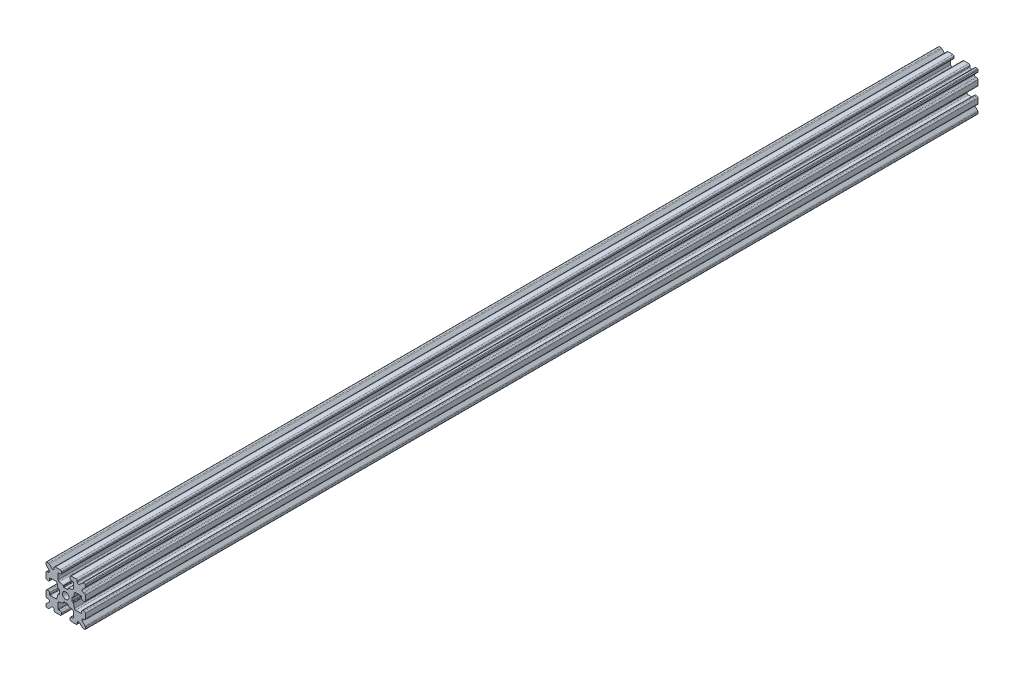
SolidWorks part; units mm, degrees
ref_plane "Alzado" through (0, 0, 0) normal (0, 0, 1) x (1, 0, 0)
ref_plane "Planta" through (0, 0, 0) normal (0, 1, 0) x (1, 0, 0)
ref_plane "Vista lateral" through (0, 0, 0) normal (1, 0, 0) x (0, 0, -1)
ref_plane "Plano1" through (0, 0, -150) normal (0, 0, -1) x (-1, 0, 0)
sketch "Croquis1" plane through (0, 0, -150) normal (0, 0, -1) x (-1, 0, 0)
  line L0 (-2.9, -5.9) -> (-2.9, -3.8003)
  line L1 (-2.5094, -3.3124) -> (-0.9818, -2.97)
  line L2 (-0.8255, -2.7749) -> (-0.8255, -2.5471)
  line L3 (-0.6255, -2.3471) -> (0.6255, -2.3471)
  line L4 (0.8255, -2.5471) -> (0.8255, -2.7749)
  line L5 (0.9818, -2.97) -> (2.5094, -3.3124)
  line L6 (2.9, -3.8003) -> (2.9, -5.9)
  line L7 (2.7, -6.1) -> (2.1, -6.1)
  line L8 (1.6, -6.6) -> (1.6, -7)
  line L9 (2.1, -7.5) -> (3.9, -7.5)
  line L10 (4.4, -7) -> (4.4, -6.6678)
  line L11 (5.2536, -6.3142) -> (6.2929, -7.3536)
  line L12 (6.6464, -7.5) -> (7.25, -7.5)
  line L13 (7.5, -7.25) -> (7.5, -6.6464)
  line L14 (7.3536, -6.2929) -> (6.3142, -5.2536)
  line L15 (6.6678, -4.4) -> (7, -4.4)
  line L16 (7.5, -3.9) -> (7.5, -2.1)
  line L17 (7, -1.6) -> (6.6, -1.6)
  line L18 (6.1, -2.1) -> (6.1, -2.7)
  line L19 (5.9, -2.9) -> (3.8003, -2.9)
  line L20 (3.3124, -2.5094) -> (2.97, -0.9818)
  line L21 (2.7749, -0.8255) -> (2.5471, -0.8255)
  line L22 (2.3471, -0.6255) -> (2.3471, 0.6255)
  line L23 (2.5471, 0.8255) -> (2.7749, 0.8255)
  line L24 (2.97, 0.9818) -> (3.3124, 2.5094)
  line L25 (3.8003, 2.9) -> (5.9, 2.9)
  line L26 (6.1, 2.7) -> (6.1, 2.1)
  line L27 (6.6, 1.6) -> (7, 1.6)
  line L28 (7.5, 2.1) -> (7.5, 3.9)
  line L29 (7, 4.4) -> (6.6678, 4.4)
  line L30 (6.3142, 5.2536) -> (7.3536, 6.2929)
  line L31 (7.5, 6.6464) -> (7.5, 7.25)
  line L32 (7.25, 7.5) -> (6.6464, 7.5)
  line L33 (6.2929, 7.3536) -> (5.2536, 6.3142)
  line L34 (4.4, 6.6678) -> (4.4, 7)
  line L35 (3.9, 7.5) -> (2.1, 7.5)
  line L36 (1.6, 7) -> (1.6, 6.6)
  line L37 (2.1, 6.1) -> (2.7, 6.1)
  line L38 (2.9, 5.9) -> (2.9, 3.8003)
  line L39 (2.5094, 3.3124) -> (0.9818, 2.97)
  line L40 (0.8255, 2.7749) -> (0.8255, 2.5471)
  line L41 (0.6255, 2.3471) -> (-0.6255, 2.3471)
  line L42 (-0.8255, 2.5471) -> (-0.8255, 2.7749)
  line L43 (-0.9818, 2.97) -> (-2.5094, 3.3124)
  line L44 (-2.9, 3.8003) -> (-2.9, 5.9)
  line L45 (-2.7, 6.1) -> (-2.1, 6.1)
  line L46 (-1.6, 6.6) -> (-1.6, 7)
  line L47 (-2.1, 7.5) -> (-3.9, 7.5)
  line L48 (-4.4, 7) -> (-4.4, 6.6678)
  line L49 (-5.2536, 6.3142) -> (-6.2929, 7.3536)
  line L50 (-6.6464, 7.5) -> (-7.25, 7.5)
  line L51 (-7.5, 7.25) -> (-7.5, 6.6464)
  line L52 (-7.3536, 6.2929) -> (-6.3142, 5.2536)
  line L53 (-6.6678, 4.4) -> (-7, 4.4)
  line L54 (-7.5, 3.9) -> (-7.5, 2.1)
  line L55 (-7, 1.6) -> (-6.6, 1.6)
  line L56 (-6.1, 2.1) -> (-6.1, 2.7)
  line L57 (-5.9, 2.9) -> (-3.8003, 2.9)
  line L58 (-3.3124, 2.5094) -> (-2.97, 0.9818)
  line L59 (-2.7749, 0.8255) -> (-2.5471, 0.8255)
  line L60 (-2.3471, 0.6255) -> (-2.3471, -0.6255)
  line L61 (-2.5471, -0.8255) -> (-2.7749, -0.8255)
  line L62 (-2.97, -0.9818) -> (-3.3124, -2.5094)
  line L63 (-3.8003, -2.9) -> (-5.9, -2.9)
  line L64 (-6.1, -2.7) -> (-6.1, -2.1)
  line L65 (-6.6, -1.6) -> (-7, -1.6)
  line L66 (-7.5, -2.1) -> (-7.5, -3.9)
  line L67 (-7, -4.4) -> (-6.6678, -4.4)
  line L68 (-6.3142, -5.2536) -> (-7.3536, -6.2929)
  line L69 (-7.5, -6.6464) -> (-7.5, -7.25)
  line L70 (-7.25, -7.5) -> (-6.6464, -7.5)
  line L71 (-6.2929, -7.3536) -> (-5.2536, -6.3142)
  line L72 (-4.4, -6.6678) -> (-4.4, -7)
  line L73 (-3.9, -7.5) -> (-2.1, -7.5)
  line L74 (-1.6, -7) -> (-1.6, -6.6)
  line L75 (-2.1, -6.1) -> (-2.7, -6.1)
  circle A0 centre (0, 0) radius 1.25
  arc A1 (-2.9, -3.8003) -> (-2.5094, -3.3124) centre (-2.4, -3.8003) cw
  arc A2 (-0.9818, -2.97) -> (-0.8255, -2.7749) centre (-1.0255, -2.7749) ccw
  arc A3 (-0.8255, -2.5471) -> (-0.6255, -2.3471) centre (-0.6255, -2.5471) cw
  arc A4 (0.6255, -2.3471) -> (0.8255, -2.5471) centre (0.6255, -2.5471) cw
  arc A5 (0.8255, -2.7749) -> (0.9818, -2.97) centre (1.0255, -2.7749) ccw
  arc A6 (2.5094, -3.3124) -> (2.9, -3.8003) centre (2.4, -3.8003) cw
  arc A7 (2.9, -5.9) -> (2.7, -6.1) centre (2.7, -5.9) cw
  arc A8 (2.1, -6.1) -> (1.6, -6.6) centre (2.1, -6.6) ccw
  arc A9 (1.6, -7) -> (2.1, -7.5) centre (2.1, -7) ccw
  arc A10 (3.9, -7.5) -> (4.4, -7) centre (3.9, -7) ccw
  arc A11 (4.4, -6.6678) -> (5.2536, -6.3142) centre (4.9, -6.6678) cw
  arc A12 (6.2929, -7.3536) -> (6.6464, -7.5) centre (6.6464, -7) ccw
  arc A13 (7.25, -7.5) -> (7.5, -7.25) centre (7.25, -7.25) ccw
  arc A14 (7.5, -6.6464) -> (7.3536, -6.2929) centre (7, -6.6464) ccw
  arc A15 (6.3142, -5.2536) -> (6.6678, -4.4) centre (6.6678, -4.9) cw
  arc A16 (7, -4.4) -> (7.5, -3.9) centre (7, -3.9) ccw
  arc A17 (7.5, -2.1) -> (7, -1.6) centre (7, -2.1) ccw
  arc A18 (6.6, -1.6) -> (6.1, -2.1) centre (6.6, -2.1) ccw
  arc A19 (6.1, -2.7) -> (5.9, -2.9) centre (5.9, -2.7) cw
  arc A20 (3.8003, -2.9) -> (3.3124, -2.5094) centre (3.8003, -2.4) cw
  arc A21 (2.97, -0.9818) -> (2.7749, -0.8255) centre (2.7749, -1.0255) ccw
  arc A22 (2.5471, -0.8255) -> (2.3471, -0.6255) centre (2.5471, -0.6255) cw
  arc A23 (2.3471, 0.6255) -> (2.5471, 0.8255) centre (2.5471, 0.6255) cw
  arc A24 (2.7749, 0.8255) -> (2.97, 0.9818) centre (2.7749, 1.0255) ccw
  arc A25 (3.3124, 2.5094) -> (3.8003, 2.9) centre (3.8003, 2.4) cw
  arc A26 (5.9, 2.9) -> (6.1, 2.7) centre (5.9, 2.7) cw
  arc A27 (6.1, 2.1) -> (6.6, 1.6) centre (6.6, 2.1) ccw
  arc A28 (7, 1.6) -> (7.5, 2.1) centre (7, 2.1) ccw
  arc A29 (7.5, 3.9) -> (7, 4.4) centre (7, 3.9) ccw
  arc A30 (6.6678, 4.4) -> (6.3142, 5.2536) centre (6.6678, 4.9) cw
  arc A31 (7.3536, 6.2929) -> (7.5, 6.6464) centre (7, 6.6464) ccw
  arc A32 (7.5, 7.25) -> (7.25, 7.5) centre (7.25, 7.25) ccw
  arc A33 (6.6464, 7.5) -> (6.2929, 7.3536) centre (6.6464, 7) ccw
  arc A34 (5.2536, 6.3142) -> (4.4, 6.6678) centre (4.9, 6.6678) cw
  arc A35 (4.4, 7) -> (3.9, 7.5) centre (3.9, 7) ccw
  arc A36 (2.1, 7.5) -> (1.6, 7) centre (2.1, 7) ccw
  arc A37 (1.6, 6.6) -> (2.1, 6.1) centre (2.1, 6.6) ccw
  arc A38 (2.7, 6.1) -> (2.9, 5.9) centre (2.7, 5.9) cw
  arc A39 (2.9, 3.8003) -> (2.5094, 3.3124) centre (2.4, 3.8003) cw
  arc A40 (0.9818, 2.97) -> (0.8255, 2.7749) centre (1.0255, 2.7749) ccw
  arc A41 (0.8255, 2.5471) -> (0.6255, 2.3471) centre (0.6255, 2.5471) cw
  arc A42 (-0.6255, 2.3471) -> (-0.8255, 2.5471) centre (-0.6255, 2.5471) cw
  arc A43 (-0.8255, 2.7749) -> (-0.9818, 2.97) centre (-1.0255, 2.7749) ccw
  arc A44 (-2.5094, 3.3124) -> (-2.9, 3.8003) centre (-2.4, 3.8003) cw
  arc A45 (-2.9, 5.9) -> (-2.7, 6.1) centre (-2.7, 5.9) cw
  arc A46 (-2.1, 6.1) -> (-1.6, 6.6) centre (-2.1, 6.6) ccw
  arc A47 (-1.6, 7) -> (-2.1, 7.5) centre (-2.1, 7) ccw
  arc A48 (-3.9, 7.5) -> (-4.4, 7) centre (-3.9, 7) ccw
  arc A49 (-4.4, 6.6678) -> (-5.2536, 6.3142) centre (-4.9, 6.6678) cw
  arc A50 (-6.2929, 7.3536) -> (-6.6464, 7.5) centre (-6.6464, 7) ccw
  arc A51 (-7.25, 7.5) -> (-7.5, 7.25) centre (-7.25, 7.25) ccw
  arc A52 (-7.5, 6.6464) -> (-7.3536, 6.2929) centre (-7, 6.6464) ccw
  arc A53 (-6.3142, 5.2536) -> (-6.6678, 4.4) centre (-6.6678, 4.9) cw
  arc A54 (-7, 4.4) -> (-7.5, 3.9) centre (-7, 3.9) ccw
  arc A55 (-7.5, 2.1) -> (-7, 1.6) centre (-7, 2.1) ccw
  arc A56 (-6.6, 1.6) -> (-6.1, 2.1) centre (-6.6, 2.1) ccw
  arc A57 (-6.1, 2.7) -> (-5.9, 2.9) centre (-5.9, 2.7) cw
  arc A58 (-3.8003, 2.9) -> (-3.3124, 2.5094) centre (-3.8003, 2.4) cw
  arc A59 (-2.97, 0.9818) -> (-2.7749, 0.8255) centre (-2.7749, 1.0255) ccw
  arc A60 (-2.5471, 0.8255) -> (-2.3471, 0.6255) centre (-2.5471, 0.6255) cw
  arc A61 (-2.3471, -0.6255) -> (-2.5471, -0.8255) centre (-2.5471, -0.6255) cw
  arc A62 (-2.7749, -0.8255) -> (-2.97, -0.9818) centre (-2.7749, -1.0255) ccw
  arc A63 (-3.3124, -2.5094) -> (-3.8003, -2.9) centre (-3.8003, -2.4) cw
  arc A64 (-5.9, -2.9) -> (-6.1, -2.7) centre (-5.9, -2.7) cw
  arc A65 (-6.1, -2.1) -> (-6.6, -1.6) centre (-6.6, -2.1) ccw
  arc A66 (-7, -1.6) -> (-7.5, -2.1) centre (-7, -2.1) ccw
  arc A67 (-7.5, -3.9) -> (-7, -4.4) centre (-7, -3.9) ccw
  arc A68 (-6.6678, -4.4) -> (-6.3142, -5.2536) centre (-6.6678, -4.9) cw
  arc A69 (-7.3536, -6.2929) -> (-7.5, -6.6464) centre (-7, -6.6464) ccw
  arc A70 (-7.5, -7.25) -> (-7.25, -7.5) centre (-7.25, -7.25) ccw
  arc A71 (-6.6464, -7.5) -> (-6.2929, -7.3536) centre (-6.6464, -7) ccw
  arc A72 (-5.2536, -6.3142) -> (-4.4, -6.6678) centre (-4.9, -6.6678) cw
  arc A73 (-4.4, -7) -> (-3.9, -7.5) centre (-3.9, -7) ccw
  arc A74 (-2.1, -7.5) -> (-1.6, -7) centre (-2.1, -7) ccw
  arc A75 (-1.6, -6.6) -> (-2.1, -6.1) centre (-2.1, -6.6) ccw
  arc A76 (-2.7, -6.1) -> (-2.9, -5.9) centre (-2.7, -5.9) cw
extrude "Saliente-Extruir1" add sketch "Croquis1" against normal blind 300
sketch "Croquis2" plane through (0, 0, 150) normal (0, 0, 1) x (1, 0, 0)
  line L76 (2.7, -6.1) -> (2.1, -6.1)
  line L77 (1.6, -6.6) -> (1.6, -7)
  line L78 (2.1, -7.5) -> (3.9, -7.5)
  line L79 (4.4, -7) -> (4.4, -6.6678)
  line L80 (5.2536, -6.3142) -> (6.2929, -7.3536)
  line L81 (6.6464, -7.5) -> (7.25, -7.5)
  line L82 (7.5, -7.25) -> (7.5, -6.6464)
  line L83 (7.3536, -6.2929) -> (6.3142, -5.2536)
  line L84 (6.6678, -4.4) -> (7, -4.4)
  line L85 (7.5, -3.9) -> (7.5, -2.1)
  line L86 (7, -1.6) -> (6.6, -1.6)
  line L87 (6.1, -2.1) -> (6.1, -2.7)
  line L88 (5.9, -2.9) -> (3.8003, -2.9)
  line L89 (3.3124, -2.5094) -> (2.97, -0.9818)
  line L90 (2.7749, -0.8255) -> (2.5471, -0.8255)
  line L91 (2.3471, -0.6255) -> (2.3471, 0.6255)
  line L92 (2.5471, 0.8255) -> (2.7749, 0.8255)
  line L93 (2.97, 0.9818) -> (3.3124, 2.5094)
  line L94 (3.8003, 2.9) -> (5.9, 2.9)
  line L95 (6.1, 2.7) -> (6.1, 2.1)
  line L96 (6.6, 1.6) -> (7, 1.6)
  line L97 (7.5, 2.1) -> (7.5, 3.9)
  line L98 (7, 4.4) -> (6.6678, 4.4)
  line L99 (6.3142, 5.2536) -> (7.3536, 6.2929)
  line L100 (7.5, 6.6464) -> (7.5, 7.25)
  line L101 (7.25, 7.5) -> (6.6464, 7.5)
  line L102 (6.2929, 7.3536) -> (5.2536, 6.3142)
  line L103 (4.4, 6.6678) -> (4.4, 7)
  line L104 (3.9, 7.5) -> (2.1, 7.5)
  line L105 (1.6, 7) -> (1.6, 6.6)
  line L106 (2.1, 6.1) -> (2.7, 6.1)
  line L107 (2.9, 5.9) -> (2.9, 3.8003)
  line L108 (2.5094, 3.3124) -> (0.9818, 2.97)
  line L109 (0.8255, 2.7749) -> (0.8255, 2.5471)
  line L110 (0.6255, 2.3471) -> (-0.6255, 2.3471)
  line L111 (-0.8255, 2.5471) -> (-0.8255, 2.7749)
  line L112 (-0.9818, 2.97) -> (-2.5094, 3.3124)
  line L113 (-2.9, 3.8003) -> (-2.9, 5.9)
  line L114 (-2.7, 6.1) -> (-2.1, 6.1)
  line L115 (-1.6, 6.6) -> (-1.6, 7)
  line L116 (-2.1, 7.5) -> (-3.9, 7.5)
  line L117 (-4.4, 7) -> (-4.4, 6.6678)
  line L118 (-5.2536, 6.3142) -> (-6.2929, 7.3536)
  line L119 (-6.6464, 7.5) -> (-7.25, 7.5)
  line L120 (-7.5, 7.25) -> (-7.5, 6.6464)
  line L121 (-7.3536, 6.2929) -> (-6.3142, 5.2536)
  line L122 (-6.6678, 4.4) -> (-7, 4.4)
  line L123 (-7.5, 3.9) -> (-7.5, 2.1)
  line L124 (-7, 1.6) -> (-6.6, 1.6)
  line L125 (-6.1, 2.1) -> (-6.1, 2.7)
  line L126 (-5.9, 2.9) -> (-3.8003, 2.9)
  line L127 (-3.3124, 2.5094) -> (-2.97, 0.9818)
  line L128 (-2.7749, 0.8255) -> (-2.5471, 0.8255)
  line L129 (-2.3471, 0.6255) -> (-2.3471, -0.6255)
  line L130 (-2.5471, -0.8255) -> (-2.7749, -0.8255)
  line L131 (-2.97, -0.9818) -> (-3.3124, -2.5094)
  line L132 (-3.8003, -2.9) -> (-5.9, -2.9)
  line L133 (-6.1, -2.7) -> (-6.1, -2.1)
  line L134 (-6.6, -1.6) -> (-7, -1.6)
  line L135 (-7.5, -2.1) -> (-7.5, -3.9)
  line L136 (-7, -4.4) -> (-6.6678, -4.4)
  line L137 (-6.3142, -5.2536) -> (-7.3536, -6.2929)
  line L138 (-7.5, -6.6464) -> (-7.5, -7.25)
  line L139 (-7.25, -7.5) -> (-6.6464, -7.5)
  line L140 (-6.2929, -7.3536) -> (-5.2536, -6.3142)
  line L141 (-4.4, -6.6678) -> (-4.4, -7)
  line L142 (-3.9, -7.5) -> (-2.1, -7.5)
  line L143 (-1.6, -7) -> (-1.6, -6.6)
  line L144 (-2.1, -6.1) -> (-2.7, -6.1)
  line L145 (-2.9, -5.9) -> (-2.9, -3.8003)
  line L146 (-2.5094, -3.3124) -> (-0.9818, -2.97)
  line L147 (-0.8255, -2.7749) -> (-0.8255, -2.5471)
  line L148 (-0.6255, -2.3471) -> (0.6255, -2.3471)
  line L149 (0.8255, -2.5471) -> (0.8255, -2.7749)
  line L150 (0.9818, -2.97) -> (2.5094, -3.3124)
  line L151 (2.9, -3.8003) -> (2.9, -5.9)
  line L152 (2.7, -6.1) -> (2.1, -6.1)
  line L153 (1.6, -6.6) -> (1.6, -7)
  line L154 (2.1, -7.5) -> (3.9, -7.5)
  line L155 (4.4, -7) -> (4.4, -6.6678)
  line L156 (5.2536, -6.3142) -> (6.2929, -7.3536)
  line L157 (6.6464, -7.5) -> (7.25, -7.5)
  line L158 (7.5, -7.25) -> (7.5, -6.6464)
  line L159 (7.3536, -6.2929) -> (6.3142, -5.2536)
  line L160 (6.6678, -4.4) -> (7, -4.4)
  line L161 (7.5, -3.9) -> (7.5, -2.1)
  line L162 (7, -1.6) -> (6.6, -1.6)
  line L163 (6.1, -2.1) -> (6.1, -2.7)
  line L164 (5.9, -2.9) -> (3.8003, -2.9)
  line L165 (3.3124, -2.5094) -> (2.97, -0.9818)
  line L166 (2.7749, -0.8255) -> (2.5471, -0.8255)
  line L167 (2.3471, -0.6255) -> (2.3471, 0.6255)
  line L168 (2.5471, 0.8255) -> (2.7749, 0.8255)
  line L169 (2.97, 0.9818) -> (3.3124, 2.5094)
  line L170 (3.8003, 2.9) -> (5.9, 2.9)
  line L171 (6.1, 2.7) -> (6.1, 2.1)
  line L172 (6.6, 1.6) -> (7, 1.6)
  line L173 (7.5, 2.1) -> (7.5, 3.9)
  line L174 (7, 4.4) -> (6.6678, 4.4)
  line L175 (6.3142, 5.2536) -> (7.3536, 6.2929)
  line L176 (7.5, 6.6464) -> (7.5, 7.25)
  line L177 (7.25, 7.5) -> (6.6464, 7.5)
  line L178 (6.2929, 7.3536) -> (5.2536, 6.3142)
  line L179 (4.4, 6.6678) -> (4.4, 7)
  line L180 (3.9, 7.5) -> (2.1, 7.5)
  line L181 (1.6, 7) -> (1.6, 6.6)
  line L182 (2.1, 6.1) -> (2.7, 6.1)
  line L183 (2.9, 5.9) -> (2.9, 3.8003)
  line L184 (2.5094, 3.3124) -> (0.9818, 2.97)
  line L185 (0.8255, 2.7749) -> (0.8255, 2.5471)
  line L186 (0.6255, 2.3471) -> (-0.6255, 2.3471)
  line L187 (-0.8255, 2.5471) -> (-0.8255, 2.7749)
  line L188 (-0.9818, 2.97) -> (-2.5094, 3.3124)
  line L189 (-2.9, 3.8003) -> (-2.9, 5.9)
  line L190 (-2.7, 6.1) -> (-2.1, 6.1)
  line L191 (-1.6, 6.6) -> (-1.6, 7)
  line L192 (-2.1, 7.5) -> (-3.9, 7.5)
  line L193 (-4.4, 7) -> (-4.4, 6.6678)
  line L194 (-5.2536, 6.3142) -> (-6.2929, 7.3536)
  line L195 (-6.6464, 7.5) -> (-7.25, 7.5)
  line L196 (-7.5, 7.25) -> (-7.5, 6.6464)
  line L197 (-7.3536, 6.2929) -> (-6.3142, 5.2536)
  line L198 (-6.6678, 4.4) -> (-7, 4.4)
  line L199 (-7.5, 3.9) -> (-7.5, 2.1)
  line L200 (-7, 1.6) -> (-6.6, 1.6)
  line L201 (-6.1, 2.1) -> (-6.1, 2.7)
  line L202 (-5.9, 2.9) -> (-3.8003, 2.9)
  line L203 (-3.3124, 2.5094) -> (-2.97, 0.9818)
  line L204 (-2.7749, 0.8255) -> (-2.5471, 0.8255)
  line L205 (-2.3471, 0.6255) -> (-2.3471, -0.6255)
  line L206 (-2.5471, -0.8255) -> (-2.7749, -0.8255)
  line L207 (-2.97, -0.9818) -> (-3.3124, -2.5094)
  line L208 (-3.8003, -2.9) -> (-5.9, -2.9)
  line L209 (-6.1, -2.7) -> (-6.1, -2.1)
  line L210 (-6.6, -1.6) -> (-7, -1.6)
  line L211 (-7.5, -2.1) -> (-7.5, -3.9)
  line L212 (-7, -4.4) -> (-6.6678, -4.4)
  line L213 (-6.3142, -5.2536) -> (-7.3536, -6.2929)
  line L214 (-7.5, -6.6464) -> (-7.5, -7.25)
  line L215 (-7.25, -7.5) -> (-6.6464, -7.5)
  line L216 (-6.2929, -7.3536) -> (-5.2536, -6.3142)
  line L217 (-4.4, -6.6678) -> (-4.4, -7)
  line L218 (-3.9, -7.5) -> (-2.1, -7.5)
  line L219 (-1.6, -7) -> (-1.6, -6.6)
  line L220 (-2.1, -6.1) -> (-2.7, -6.1)
  line L221 (-2.9, -5.9) -> (-2.9, -3.8003)
  line L222 (-2.5094, -3.3124) -> (-0.9818, -2.97)
  line L223 (-0.8255, -2.7749) -> (-0.8255, -2.5471)
  line L224 (-0.6255, -2.3471) -> (0.6255, -2.3471)
  line L225 (0.8255, -2.5471) -> (0.8255, -2.7749)
  line L226 (0.9818, -2.97) -> (2.5094, -3.3124)
  line L227 (2.9, -3.8003) -> (2.9, -5.9)
  circle A0 centre (0, 0) radius 1.25 construction
  circle A1 centre (0, 0) radius 1.25
  arc A76 (2.7, -6.1) -> (2.9, -5.9) centre (2.7, -5.9) ccw
  arc A77 (2.1, -6.1) -> (1.6, -6.6) centre (2.1, -6.6) ccw
  arc A78 (1.6, -7) -> (2.1, -7.5) centre (2.1, -7) ccw
  arc A79 (3.9, -7.5) -> (4.4, -7) centre (3.9, -7) ccw
  arc A80 (5.2536, -6.3142) -> (4.4, -6.6678) centre (4.9, -6.6678) ccw
  arc A81 (6.2929, -7.3536) -> (6.6464, -7.5) centre (6.6464, -7) ccw
  arc A82 (7.25, -7.5) -> (7.5, -7.25) centre (7.25, -7.25) ccw
  arc A83 (7.5, -6.6464) -> (7.3536, -6.2929) centre (7, -6.6464) ccw
  arc A84 (6.6678, -4.4) -> (6.3142, -5.2536) centre (6.6678, -4.9) ccw
  arc A85 (7, -4.4) -> (7.5, -3.9) centre (7, -3.9) ccw
  arc A86 (7.5, -2.1) -> (7, -1.6) centre (7, -2.1) ccw
  arc A87 (6.6, -1.6) -> (6.1, -2.1) centre (6.6, -2.1) ccw
  arc A88 (5.9, -2.9) -> (6.1, -2.7) centre (5.9, -2.7) ccw
  arc A89 (3.3124, -2.5094) -> (3.8003, -2.9) centre (3.8003, -2.4) ccw
  arc A90 (2.97, -0.9818) -> (2.7749, -0.8255) centre (2.7749, -1.0255) ccw
  arc A91 (2.3471, -0.6255) -> (2.5471, -0.8255) centre (2.5471, -0.6255) ccw
  arc A92 (2.5471, 0.8255) -> (2.3471, 0.6255) centre (2.5471, 0.6255) ccw
  arc A93 (2.7749, 0.8255) -> (2.97, 0.9818) centre (2.7749, 1.0255) ccw
  arc A94 (3.8003, 2.9) -> (3.3124, 2.5094) centre (3.8003, 2.4) ccw
  arc A95 (6.1, 2.7) -> (5.9, 2.9) centre (5.9, 2.7) ccw
  arc A96 (6.1, 2.1) -> (6.6, 1.6) centre (6.6, 2.1) ccw
  arc A97 (7, 1.6) -> (7.5, 2.1) centre (7, 2.1) ccw
  arc A98 (7.5, 3.9) -> (7, 4.4) centre (7, 3.9) ccw
  arc A99 (6.3142, 5.2536) -> (6.6678, 4.4) centre (6.6678, 4.9) ccw
  arc A100 (7.3536, 6.2929) -> (7.5, 6.6464) centre (7, 6.6464) ccw
  arc A101 (7.5, 7.25) -> (7.25, 7.5) centre (7.25, 7.25) ccw
  arc A102 (6.6464, 7.5) -> (6.2929, 7.3536) centre (6.6464, 7) ccw
  arc A103 (4.4, 6.6678) -> (5.2536, 6.3142) centre (4.9, 6.6678) ccw
  arc A104 (4.4, 7) -> (3.9, 7.5) centre (3.9, 7) ccw
  arc A105 (2.1, 7.5) -> (1.6, 7) centre (2.1, 7) ccw
  arc A106 (1.6, 6.6) -> (2.1, 6.1) centre (2.1, 6.6) ccw
  arc A107 (2.9, 5.9) -> (2.7, 6.1) centre (2.7, 5.9) ccw
  arc A108 (2.5094, 3.3124) -> (2.9, 3.8003) centre (2.4, 3.8003) ccw
  arc A109 (0.9818, 2.97) -> (0.8255, 2.7749) centre (1.0255, 2.7749) ccw
  arc A110 (0.6255, 2.3471) -> (0.8255, 2.5471) centre (0.6255, 2.5471) ccw
  arc A111 (-0.8255, 2.5471) -> (-0.6255, 2.3471) centre (-0.6255, 2.5471) ccw
  arc A112 (-0.8255, 2.7749) -> (-0.9818, 2.97) centre (-1.0255, 2.7749) ccw
  arc A113 (-2.9, 3.8003) -> (-2.5094, 3.3124) centre (-2.4, 3.8003) ccw
  arc A114 (-2.7, 6.1) -> (-2.9, 5.9) centre (-2.7, 5.9) ccw
  arc A115 (-2.1, 6.1) -> (-1.6, 6.6) centre (-2.1, 6.6) ccw
  arc A116 (-1.6, 7) -> (-2.1, 7.5) centre (-2.1, 7) ccw
  arc A117 (-3.9, 7.5) -> (-4.4, 7) centre (-3.9, 7) ccw
  arc A118 (-5.2536, 6.3142) -> (-4.4, 6.6678) centre (-4.9, 6.6678) ccw
  arc A119 (-6.2929, 7.3536) -> (-6.6464, 7.5) centre (-6.6464, 7) ccw
  arc A120 (-7.25, 7.5) -> (-7.5, 7.25) centre (-7.25, 7.25) ccw
  arc A121 (-7.5, 6.6464) -> (-7.3536, 6.2929) centre (-7, 6.6464) ccw
  arc A122 (-6.6678, 4.4) -> (-6.3142, 5.2536) centre (-6.6678, 4.9) ccw
  arc A123 (-7, 4.4) -> (-7.5, 3.9) centre (-7, 3.9) ccw
  arc A124 (-7.5, 2.1) -> (-7, 1.6) centre (-7, 2.1) ccw
  arc A125 (-6.6, 1.6) -> (-6.1, 2.1) centre (-6.6, 2.1) ccw
  arc A126 (-5.9, 2.9) -> (-6.1, 2.7) centre (-5.9, 2.7) ccw
  arc A127 (-3.3124, 2.5094) -> (-3.8003, 2.9) centre (-3.8003, 2.4) ccw
  arc A128 (-2.97, 0.9818) -> (-2.7749, 0.8255) centre (-2.7749, 1.0255) ccw
  arc A129 (-2.3471, 0.6255) -> (-2.5471, 0.8255) centre (-2.5471, 0.6255) ccw
  arc A130 (-2.5471, -0.8255) -> (-2.3471, -0.6255) centre (-2.5471, -0.6255) ccw
  arc A131 (-2.7749, -0.8255) -> (-2.97, -0.9818) centre (-2.7749, -1.0255) ccw
  arc A132 (-3.8003, -2.9) -> (-3.3124, -2.5094) centre (-3.8003, -2.4) ccw
  arc A133 (-6.1, -2.7) -> (-5.9, -2.9) centre (-5.9, -2.7) ccw
  arc A134 (-6.1, -2.1) -> (-6.6, -1.6) centre (-6.6, -2.1) ccw
  arc A135 (-7, -1.6) -> (-7.5, -2.1) centre (-7, -2.1) ccw
  arc A136 (-7.5, -3.9) -> (-7, -4.4) centre (-7, -3.9) ccw
  arc A137 (-6.3142, -5.2536) -> (-6.6678, -4.4) centre (-6.6678, -4.9) ccw
  arc A138 (-7.3536, -6.2929) -> (-7.5, -6.6464) centre (-7, -6.6464) ccw
  arc A139 (-7.5, -7.25) -> (-7.25, -7.5) centre (-7.25, -7.25) ccw
  arc A140 (-6.6464, -7.5) -> (-6.2929, -7.3536) centre (-6.6464, -7) ccw
  arc A141 (-4.4, -6.6678) -> (-5.2536, -6.3142) centre (-4.9, -6.6678) ccw
  arc A142 (-4.4, -7) -> (-3.9, -7.5) centre (-3.9, -7) ccw
  arc A143 (-2.1, -7.5) -> (-1.6, -7) centre (-2.1, -7) ccw
  arc A144 (-1.6, -6.6) -> (-2.1, -6.1) centre (-2.1, -6.6) ccw
  arc A145 (-2.9, -5.9) -> (-2.7, -6.1) centre (-2.7, -5.9) ccw
  arc A146 (-2.5094, -3.3124) -> (-2.9, -3.8003) centre (-2.4, -3.8003) ccw
  arc A147 (-0.9818, -2.97) -> (-0.8255, -2.7749) centre (-1.0255, -2.7749) ccw
  arc A148 (-0.6255, -2.3471) -> (-0.8255, -2.5471) centre (-0.6255, -2.5471) ccw
  arc A149 (0.8255, -2.5471) -> (0.6255, -2.3471) centre (0.6255, -2.5471) ccw
  arc A150 (0.8255, -2.7749) -> (0.9818, -2.97) centre (1.0255, -2.7749) ccw
  arc A151 (2.9, -3.8003) -> (2.5094, -3.3124) centre (2.4, -3.8003) ccw
  arc A152 (2.7, -6.1) -> (2.9, -5.9) centre (2.7, -5.9) ccw
  arc A153 (2.1, -6.1) -> (1.6, -6.6) centre (2.1, -6.6) ccw
  arc A154 (1.6, -7) -> (2.1, -7.5) centre (2.1, -7) ccw
  arc A155 (3.9, -7.5) -> (4.4, -7) centre (3.9, -7) ccw
  arc A156 (5.2536, -6.3142) -> (4.4, -6.6678) centre (4.9, -6.6678) ccw
  arc A157 (6.2929, -7.3536) -> (6.6464, -7.5) centre (6.6464, -7) ccw
  arc A158 (7.25, -7.5) -> (7.5, -7.25) centre (7.25, -7.25) ccw
  arc A159 (7.5, -6.6464) -> (7.3536, -6.2929) centre (7, -6.6464) ccw
  arc A160 (6.6678, -4.4) -> (6.3142, -5.2536) centre (6.6678, -4.9) ccw
  arc A161 (7, -4.4) -> (7.5, -3.9) centre (7, -3.9) ccw
  arc A162 (7.5, -2.1) -> (7, -1.6) centre (7, -2.1) ccw
  arc A163 (6.6, -1.6) -> (6.1, -2.1) centre (6.6, -2.1) ccw
  arc A164 (5.9, -2.9) -> (6.1, -2.7) centre (5.9, -2.7) ccw
  arc A165 (3.3124, -2.5094) -> (3.8003, -2.9) centre (3.8003, -2.4) ccw
  arc A166 (2.97, -0.9818) -> (2.7749, -0.8255) centre (2.7749, -1.0255) ccw
  arc A167 (2.3471, -0.6255) -> (2.5471, -0.8255) centre (2.5471, -0.6255) ccw
  arc A168 (2.5471, 0.8255) -> (2.3471, 0.6255) centre (2.5471, 0.6255) ccw
  arc A169 (2.7749, 0.8255) -> (2.97, 0.9818) centre (2.7749, 1.0255) ccw
  arc A170 (3.8003, 2.9) -> (3.3124, 2.5094) centre (3.8003, 2.4) ccw
  arc A171 (6.1, 2.7) -> (5.9, 2.9) centre (5.9, 2.7) ccw
  arc A172 (6.1, 2.1) -> (6.6, 1.6) centre (6.6, 2.1) ccw
  arc A173 (7, 1.6) -> (7.5, 2.1) centre (7, 2.1) ccw
  arc A174 (7.5, 3.9) -> (7, 4.4) centre (7, 3.9) ccw
  arc A175 (6.3142, 5.2536) -> (6.6678, 4.4) centre (6.6678, 4.9) ccw
  arc A176 (7.3536, 6.2929) -> (7.5, 6.6464) centre (7, 6.6464) ccw
  arc A177 (7.5, 7.25) -> (7.25, 7.5) centre (7.25, 7.25) ccw
  arc A178 (6.6464, 7.5) -> (6.2929, 7.3536) centre (6.6464, 7) ccw
  arc A179 (4.4, 6.6678) -> (5.2536, 6.3142) centre (4.9, 6.6678) ccw
  arc A180 (4.4, 7) -> (3.9, 7.5) centre (3.9, 7) ccw
  arc A181 (2.1, 7.5) -> (1.6, 7) centre (2.1, 7) ccw
  arc A182 (1.6, 6.6) -> (2.1, 6.1) centre (2.1, 6.6) ccw
  arc A183 (2.9, 5.9) -> (2.7, 6.1) centre (2.7, 5.9) ccw
  arc A184 (2.5094, 3.3124) -> (2.9, 3.8003) centre (2.4, 3.8003) ccw
  arc A185 (0.9818, 2.97) -> (0.8255, 2.7749) centre (1.0255, 2.7749) ccw
  arc A186 (0.6255, 2.3471) -> (0.8255, 2.5471) centre (0.6255, 2.5471) ccw
  arc A187 (-0.8255, 2.5471) -> (-0.6255, 2.3471) centre (-0.6255, 2.5471) ccw
  arc A188 (-0.8255, 2.7749) -> (-0.9818, 2.97) centre (-1.0255, 2.7749) ccw
  arc A189 (-2.9, 3.8003) -> (-2.5094, 3.3124) centre (-2.4, 3.8003) ccw
  arc A190 (-2.7, 6.1) -> (-2.9, 5.9) centre (-2.7, 5.9) ccw
  arc A191 (-2.1, 6.1) -> (-1.6, 6.6) centre (-2.1, 6.6) ccw
  arc A192 (-1.6, 7) -> (-2.1, 7.5) centre (-2.1, 7) ccw
  arc A193 (-3.9, 7.5) -> (-4.4, 7) centre (-3.9, 7) ccw
  arc A194 (-5.2536, 6.3142) -> (-4.4, 6.6678) centre (-4.9, 6.6678) ccw
  arc A195 (-6.2929, 7.3536) -> (-6.6464, 7.5) centre (-6.6464, 7) ccw
  arc A196 (-7.25, 7.5) -> (-7.5, 7.25) centre (-7.25, 7.25) ccw
  arc A197 (-7.5, 6.6464) -> (-7.3536, 6.2929) centre (-7, 6.6464) ccw
  arc A198 (-6.6678, 4.4) -> (-6.3142, 5.2536) centre (-6.6678, 4.9) ccw
  arc A199 (-7, 4.4) -> (-7.5, 3.9) centre (-7, 3.9) ccw
  arc A200 (-7.5, 2.1) -> (-7, 1.6) centre (-7, 2.1) ccw
  arc A201 (-6.6, 1.6) -> (-6.1, 2.1) centre (-6.6, 2.1) ccw
  arc A202 (-5.9, 2.9) -> (-6.1, 2.7) centre (-5.9, 2.7) ccw
  arc A203 (-3.3124, 2.5094) -> (-3.8003, 2.9) centre (-3.8003, 2.4) ccw
  arc A204 (-2.97, 0.9818) -> (-2.7749, 0.8255) centre (-2.7749, 1.0255) ccw
  arc A205 (-2.3471, 0.6255) -> (-2.5471, 0.8255) centre (-2.5471, 0.6255) ccw
  arc A206 (-2.5471, -0.8255) -> (-2.3471, -0.6255) centre (-2.5471, -0.6255) ccw
  arc A207 (-2.7749, -0.8255) -> (-2.97, -0.9818) centre (-2.7749, -1.0255) ccw
  arc A208 (-3.8003, -2.9) -> (-3.3124, -2.5094) centre (-3.8003, -2.4) ccw
  arc A209 (-6.1, -2.7) -> (-5.9, -2.9) centre (-5.9, -2.7) ccw
  arc A210 (-6.1, -2.1) -> (-6.6, -1.6) centre (-6.6, -2.1) ccw
  arc A211 (-7, -1.6) -> (-7.5, -2.1) centre (-7, -2.1) ccw
  arc A212 (-7.5, -3.9) -> (-7, -4.4) centre (-7, -3.9) ccw
  arc A213 (-6.3142, -5.2536) -> (-6.6678, -4.4) centre (-6.6678, -4.9) ccw
  arc A214 (-7.3536, -6.2929) -> (-7.5, -6.6464) centre (-7, -6.6464) ccw
  arc A215 (-7.5, -7.25) -> (-7.25, -7.5) centre (-7.25, -7.25) ccw
  arc A216 (-6.6464, -7.5) -> (-6.2929, -7.3536) centre (-6.6464, -7) ccw
  arc A217 (-4.4, -6.6678) -> (-5.2536, -6.3142) centre (-4.9, -6.6678) ccw
  arc A218 (-4.4, -7) -> (-3.9, -7.5) centre (-3.9, -7) ccw
  arc A219 (-2.1, -7.5) -> (-1.6, -7) centre (-2.1, -7) ccw
  arc A220 (-1.6, -6.6) -> (-2.1, -6.1) centre (-2.1, -6.6) ccw
  arc A221 (-2.9, -5.9) -> (-2.7, -6.1) centre (-2.7, -5.9) ccw
  arc A222 (-2.5094, -3.3124) -> (-2.9, -3.8003) centre (-2.4, -3.8003) ccw
  arc A223 (-0.9818, -2.97) -> (-0.8255, -2.7749) centre (-1.0255, -2.7749) ccw
  arc A224 (-0.6255, -2.3471) -> (-0.8255, -2.5471) centre (-0.6255, -2.5471) ccw
  arc A225 (0.8255, -2.5471) -> (0.6255, -2.3471) centre (0.6255, -2.5471) ccw
  arc A226 (0.8255, -2.7749) -> (0.9818, -2.97) centre (1.0255, -2.7749) ccw
  arc A227 (2.9, -3.8003) -> (2.5094, -3.3124) centre (2.4, -3.8003) ccw
  dimension "D1" = 0
extrude "Saliente-Extruir2" add sketch "Croquis2" along normal blind 40
